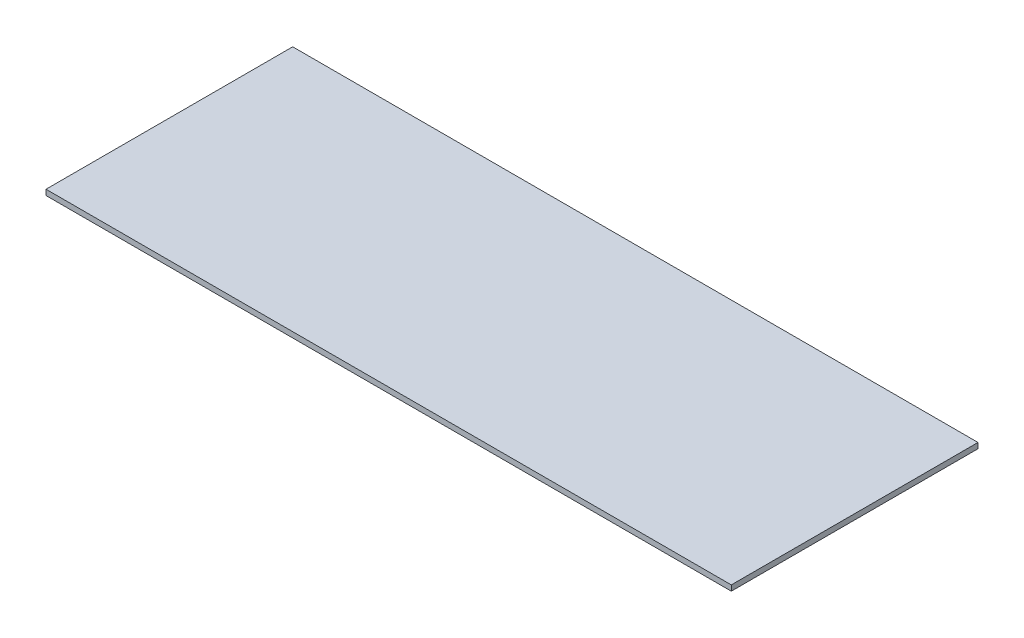
SolidWorks part; units mm, degrees
material "Maple"
ref_plane "Front Plane" through (0, 0, 0) normal (0, 0, 1) x (1, 0, 0)
ref_plane "Top Plane" through (0, 0, 0) normal (0, 1, 0) x (1, 0, 0)
ref_plane "Right Plane" through (0, 0, 0) normal (1, 0, 0) x (0, 0, -1)
sketch "Sketch1" plane through (0, 0, 0) normal (0, 1, 0) x (1, 0, 0)
  line L1 (-625, 225) -> (625, 225)
  line L2 (-625, 225) -> (-625, -225)
  line L3 (-625, -225) -> (625, -225)
  line L4 (625, 225) -> (625, -225)
  line L5 (-625, 225) -> (625, -225) construction
  line L6 (-625, -225) -> (625, 225) construction
  point P0 (0, 0)
  dimension "D1" = 450
  dimension "D2" = 1250
extrude "Boss-Extrude1" add sketch "Sketch1" along normal blind 10
